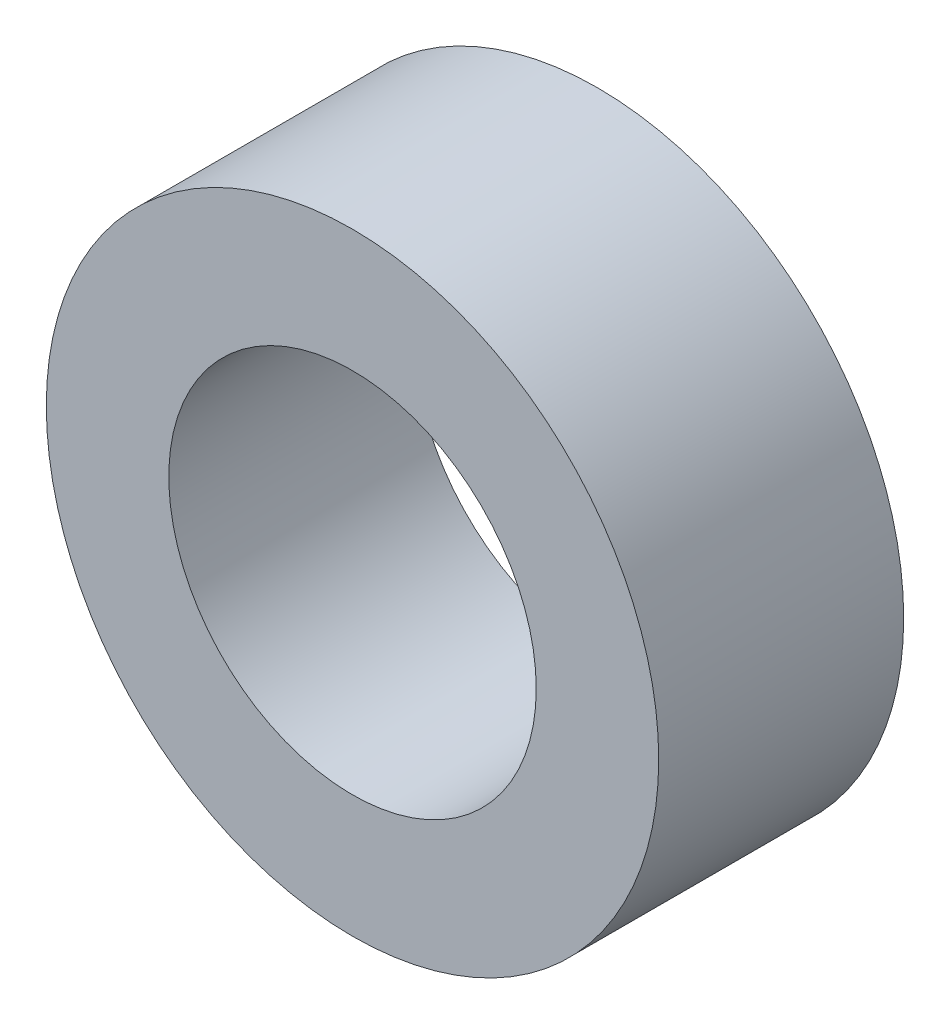
SolidWorks part; units mm, degrees
material "Birch Plywood"
ref_plane "Front Plane" through (0, 0, 0) normal (0, 0, 1) x (1, 0, 0)
ref_plane "Top Plane" through (0, 0, 0) normal (0, 1, 0) x (1, 0, 0)
ref_plane "Right Plane" through (0, 0, 0) normal (1, 0, 0) x (0, 0, -1)
sketch "Sketch1" plane through (0, 0, 0) normal (0, 0, 1) x (1, 0, 0)
  circle A0 centre (0, 0) radius 7.9375
  circle A1 centre (0, 0) radius 4.7625
  dimension "D1" = 9.525
  dimension "D2" = 15.875
extrude "Boss-Extrude1" add sketch "Sketch1" along normal blind 6.35
